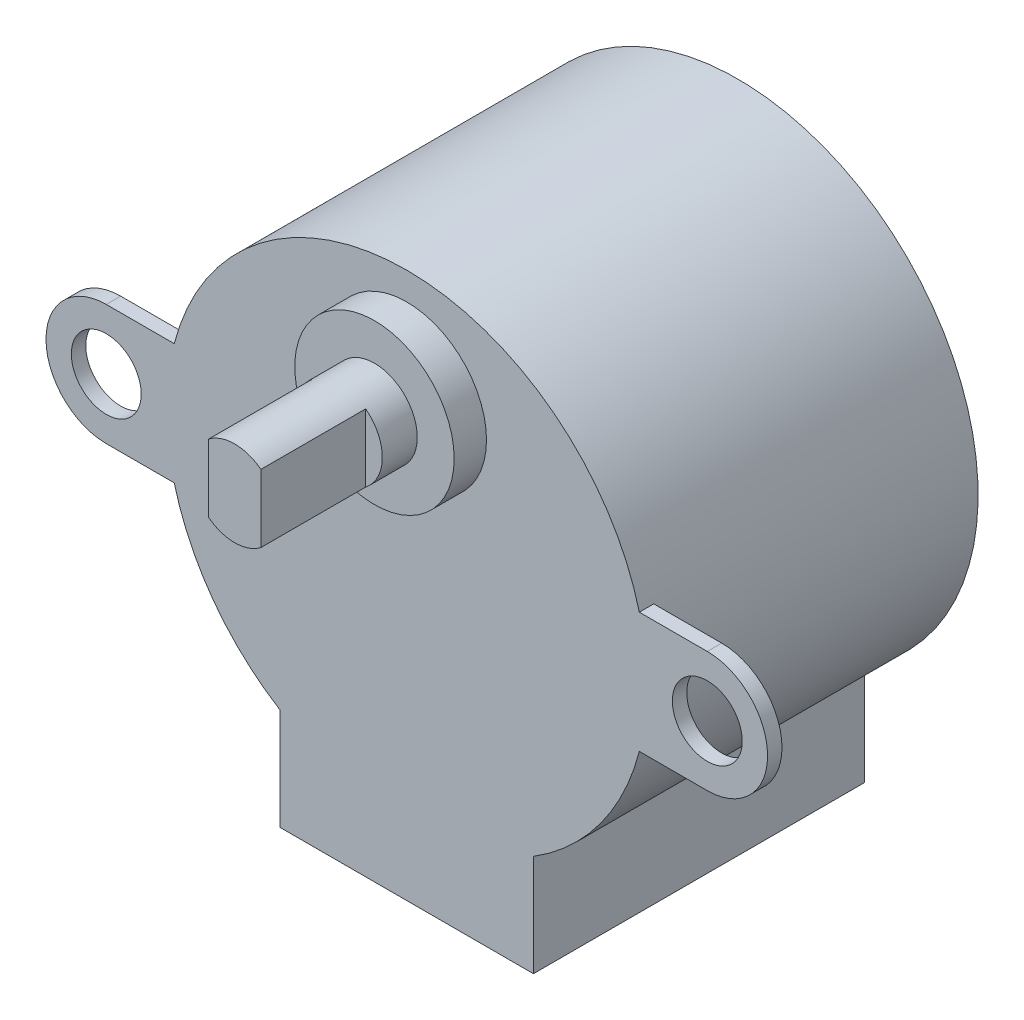
SolidWorks part; units mm, degrees
ref_plane "Front Plane" through (0, 0, 0) normal (0, 0, 1) x (1, 0, 0)
ref_plane "Top Plane" through (0, 0, 0) normal (0, 1, 0) x (1, 0, 0)
ref_plane "Right Plane" through (0, 0, 0) normal (1, 0, 0) x (0, 0, -1)
sketch "Sketch1" plane through (0, 0, 0) normal (0, 0, 1) x (1, 0, 0)
  line L0 (-7.366, -17.78) -> (7.366, -17.78)
  line L3 (-7.366, -11.8703) -> (-7.366, -17.78)
  line L5 (7.366, -11.8703) -> (7.366, -17.78)
  arc A0 (7.366, -11.8703) -> (-7.366, -11.8703) centre (0, 0) ccw
  dimension "D1" = 27.94
  dimension "D2" = 3.81
extrude "Boss-Extrude1" add sketch "Sketch1" along normal blind 19.2532
sketch "Sketch2" plane through (0, 0, 19.2532) normal (0, 0, 1) x (1, 0, 0)
  line L0 (0, 0) -> (12.5609, 0) construction
  line L1 (0, 0) -> (0, 9.396) construction
  line L3 (-13.5231, -3.5052) -> (-17.4752, -3.5052)
  line L5 (-13.5231, 3.5052) -> (-17.4752, 3.5052)
  line L7 (13.5231, 3.5052) -> (17.4752, 3.5052)
  line L8 (13.5231, -3.5052) -> (17.4752, -3.5052)
  arc A0 (-17.4752, 3.5052) -> (-17.4752, -3.5052) centre (-17.4752, 0) ccw
  arc A1 (-13.5231, 3.5052) -> (-13.5231, -3.5052) centre (0, 0) ccw
  circle A3 centre (-17.4752, 0) radius 2.032
  circle A4 centre (17.4752, 0) radius 2.032
  arc A5 (13.5231, 3.5052) -> (13.5231, -3.5052) centre (0, 0) cw
  arc A6 (17.4752, 3.5052) -> (17.4752, -3.5052) centre (17.4752, 0) cw
  point P3 (-13.97, 0)
  point P6 (-20.9804, 0)
  dimension "D2" = 4.064
  dimension "D1" = 7.0104
extrude "Boss-Extrude2" add sketch "Sketch2" against normal blind 0.8382
sketch "Sketch3" plane through (0, 0, 19.2532) normal (0, 0, 1) x (1, 0, 0)
  circle A0 centre (0, 7.7343) radius 4.6355
  arc A1 (13.5231, 3.5052) -> (-13.5231, 3.5052) centre (0, 0) ccw construction
  point P5 (0, 13.97)
  dimension "D1" = 9.271
  dimension "D2" = 1.6002
extrude "Boss-Extrude3" add sketch "Sketch3" along normal blind 1.8796
sketch "Sketch4" plane through (0, 0, 21.1328) normal (0, 0, 1) x (1, 0, 0)
  circle A0 centre (0, 7.7343) radius 2.4892
  dimension "D1" = 4.9784
extrude "Boss-Extrude4" add sketch "Sketch4" along normal blind 8.128
sketch "Sketch5" plane through (0, 0, 29.2608) normal (0, 0, 1) x (1, 0, 0)
  line L0 (-1.524, 9.7024) -> (-1.524, 5.7662)
  line L5 (0, 7.7343) -> (0, 9.1406) construction
  line L6 (1.524, 9.7024) -> (1.524, 5.7662)
  circle A0 centre (0, 7.7343) radius 2.4892 construction
  arc A1 (-1.524, 9.7024) -> (-1.524, 5.7662) centre (0, 7.7343) ccw
  arc A2 (1.524, 9.7024) -> (1.524, 5.7662) centre (0, 7.7343) cw
  point P0 (0, 7.7343)
extrude "Cut-Extrude1" cut sketch "Sketch5" against normal blind 6.096
sketch "Sketch6" plane through (0, 0, 29.2608) normal (0, 0, 1) x (1, 0, 0)
  point P0 (0, 7.7343)
